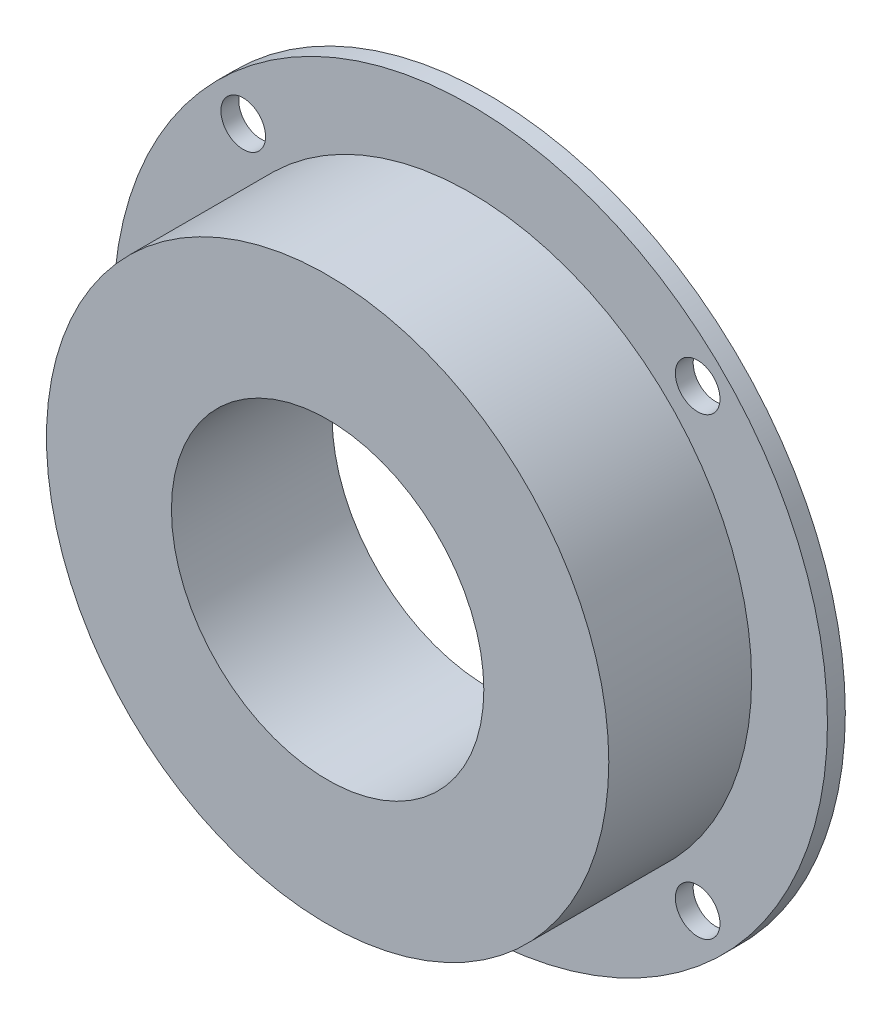
SolidWorks part; units mm, degrees
ref_plane "Front Plane" through (0, 0, 0) normal (0, 0, 1) x (1, 0, 0)
ref_plane "Top Plane" through (0, 0, 0) normal (0, 1, 0) x (1, 0, 0)
ref_plane "Right Plane" through (0, 0, 0) normal (1, 0, 0) x (0, 0, -1)
sketch "Sketch2" plane through (0, 0, 0) normal (0, 0, 1) x (1, 0, 0)
  circle A1 centre (0, 0) radius 40
  circle A2 centre (0, 0) radius 17.5
  dimension "D1" = 35
  dimension "D2" = 80
extrude "Boss-Extrude1" add sketch "Sketch2" along normal blind 2
sketch "Sketch3" plane through (0, 0, 2) normal (0, 0, 1) x (1, 0, 0)
  circle A0 centre (0, 0) radius 31.5
  circle A1 centre (0, 0) radius 17.5
  dimension "D1" = 63
extrude "Boss-Extrude2" add sketch "Sketch3" along normal blind 16
sketch "Sketch5" plane through (0, 0, 2) normal (0, 0, 1) x (1, 0, 0)
  line L0 (0, 0) -> (40, 0) construction
  line L1 (0, 0) -> (25.4558, 25.4558) construction
  circle A0 centre (0, 0) radius 36 construction
  circle A1 centre (0, 0) radius 40 construction
  circle A2 centre (25.4558, 25.4558) radius 2.5
  circle A3 centre (25.4558, -25.4558) radius 2.5
  circle A4 centre (-25.4558, -25.4558) radius 2.5
  circle A5 centre (-25.4558, 25.4558) radius 2.5
  dimension "D1" = 72
  dimension "D2" = 45
  dimension "D3" = 5
  dimension "D4" = 4
extrude "Cut-Extrude1" cut sketch "Sketch5" against normal through all
